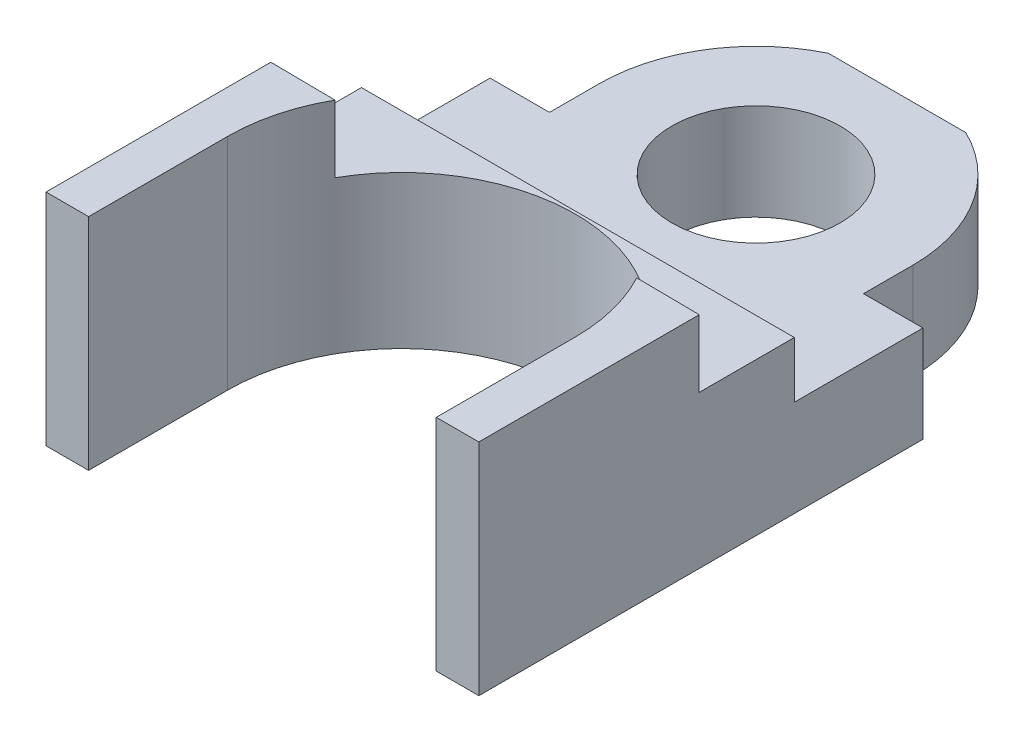
SolidWorks part; units mm, degrees
ref_plane "前视基准面" through (0, 0, 0) normal (0, 0, 1) x (1, 0, 0)
ref_plane "上视基准面" through (0, 0, 0) normal (0, 1, 0) x (1, 0, 0)
ref_plane "右视基准面" through (0, 0, 0) normal (1, 0, 0) x (0, 0, -1)
sketch "草图1" plane through (0, 0, 0) normal (0, 1, 0) x (1, 0, 0)
  line L0 (7.6476, 14.2341) -> (1.5189, 14.2341)
  line L1 (-5.0668, 5.7341) -> (-5.0668, -14.0659)
  line L2 (-5.0668, -14.0659) -> (-3.1668, -14.0659)
  line L3 (14.2332, -14.0659) -> (14.2332, 5.7341)
  line L4 (4.5832, -29.4175) -> (4.5832, 27.7537) construction
  line L5 (-5.0668, 5.7341) -> (-2.4168, 5.7341)
  line L6 (-2.4168, 7.9404) -> (-2.4168, 5.7341)
  line L7 (11.5832, 7.9404) -> (11.5832, 5.7341)
  line L8 (-5.0668, 5.7341) -> (-2.4168, 5.7341)
  line L9 (11.5832, 5.7341) -> (14.2332, 5.7341)
  line L10 (-3.1668, -7.8648) -> (-3.1668, -14.0659)
  line L11 (12.3332, -7.8648) -> (12.3332, -14.0659)
  line L12 (12.3332, -14.0659) -> (14.2332, -14.0659)
  circle A1 centre (4.5832, 7.9404) radius 3.75
  arc A2 (12.3332, -7.8648) -> (-3.1668, -7.8648) centre (4.5832, -7.8648) ccw
  arc A3 (11.5832, 7.9404) -> (7.6476, 14.2341) centre (4.5832, 7.9404) ccw
  arc A4 (1.5189, 14.2341) -> (-2.4168, 7.9404) centre (4.5832, 7.9404) ccw
  dimension "D4" = 7.5
  dimension "D6" = 15.5
  dimension "D2" = 19.3
  dimension "D5" = 8.5
extrude "凸台-拉伸2" add sketch "草图1" along normal blind 9.8 contours A2 L4 A1 L0 A4 L6 L5 L1 L2 L10 | L4 A2 L11 L12 L3 L9 L7 A3 L0 A1
sketch "草图2" plane through (0, 9.8, 0) normal (0, 1, 0) x (1, 0, 0)
  line L0 (-7.5788, -4.0163) -> (16.0851, -4.2595)
  line L1 (16.0851, -4.2595) -> (16.0851, 14.9913)
  line L2 (16.0851, 14.9913) -> (-7.5788, 14.9913)
  line L3 (-7.5788, 14.9913) -> (-7.5788, -4.0163)
extrude "切除-拉伸1" cut sketch "草图2" against normal blind 3
sketch "草图3" plane through (0, 6.8, 0) normal (0, 1, 0) x (1, 0, 0)
  line L0 (-9.7506, 0) -> (19.9017, 0)
  line L1 (19.9017, 0) -> (19.9017, 15.4708)
  line L2 (19.9017, 15.4708) -> (-9.7506, 15.7627)
  line L3 (-9.7506, 15.7627) -> (-9.7506, 0)
ref_plane "基准面6" through (-5.0668, 9.8, 4.0421) normal (0.9999, 0, 0.0103) x (0.0103, 0, -0.9999)
extrude "切除-拉伸2" cut sketch "草图3" against normal blind 2.5 contours L0 L1 L2 L3
